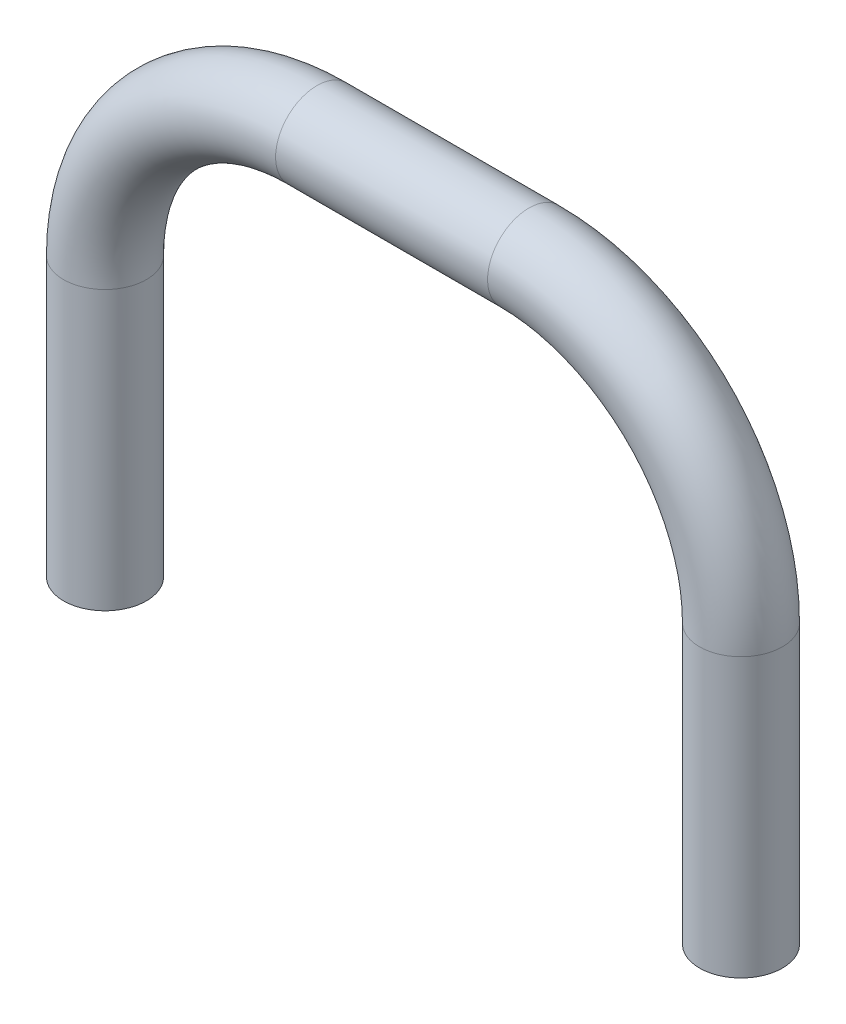
SolidWorks part; units mm, degrees
ref_plane "Front Plane" through (0, 0, 0) normal (0, 0, 1) x (1, 0, 0)
ref_plane "Top Plane" through (0, 0, 0) normal (0, 1, 0) x (1, 0, 0)
ref_plane "Right Plane" through (0, 0, 0) normal (1, 0, 0) x (0, 0, -1)
sketch "Sketch1" plane through (0, 0, 0) normal (0, 0, 1) x (1, 0, 0)
  line L0 (0, 0) -> (0, 266.7)
  line L1 (203.2, 469.9) -> (406.4, 469.9)
  line L2 (609.6, 266.7) -> (609.6, 0)
  arc A0 (203.2, 469.9) -> (0, 266.7) centre (203.2, 266.7) ccw
  arc A1 (406.4, 469.9) -> (609.6, 266.7) centre (406.4, 266.7) cw
  point P7 (0, 469.9)
  point P10 (609.6, 469.9)
  dimension "D4" = 203.2
  dimension "D1" = 609.6
  dimension "D2" = 266.7
  dimension "D3" = 266.7
  dimension "D5" = 266.7
sketch "Sketch2" plane through (0, 0, 0) normal (0, 1, 0) x (1, 0, 0)
  circle A0 centre (0, 0) radius 39.6875
  dimension "D1" = 79.375
sweep "Sweep1" add profiles "Sketch2" path "Sketch1"
sketch "Sketch3" plane through (0, 0, 0) normal (0, -1, 0) x (1, 0, 0)
  circle A0 centre (0, 0) radius 38.1
  circle A1 centre (0, 0) radius 39.6875 construction
  dimension "D1" = 1.5875
extrude "Cut-Extrude1" cut sketch "Sketch3" against normal blind 256.54
sketch "Sketch4" plane through (0, 0, 0) normal (0, -1, 0) x (1, 0, 0)
  circle A0 centre (609.6, 0) radius 38.1
  circle A1 centre (609.6, 0) radius 39.6875 construction
  dimension "D1" = 1.5875
extrude "Cut-Extrude2" cut sketch "Sketch4" against normal blind 261.62
